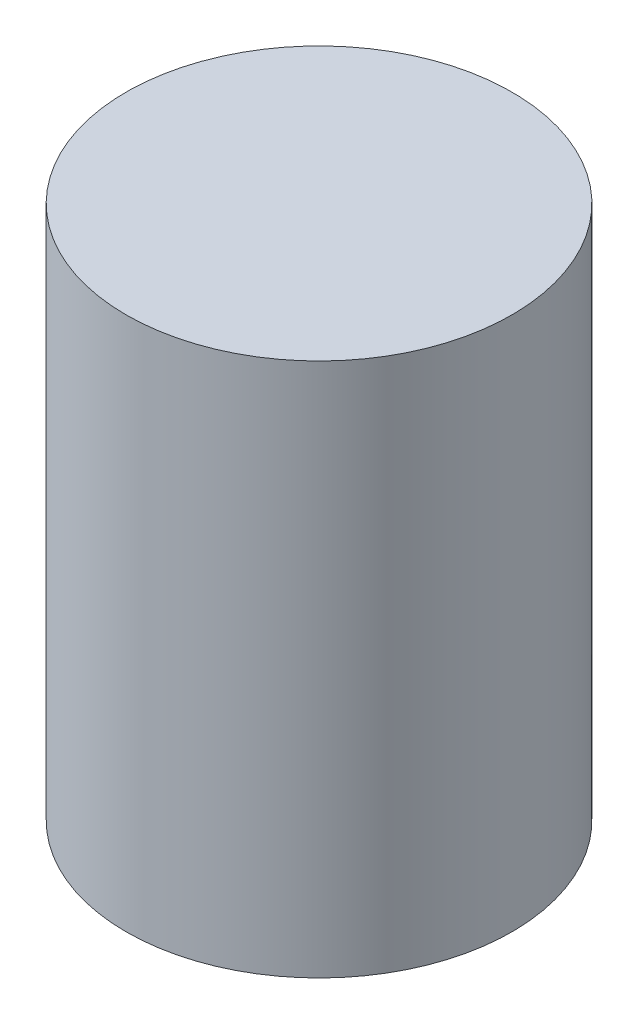
SolidWorks part; units mm, degrees
ref_plane "Спереди" through (0, 0, 0) normal (0, 0, 1) x (1, 0, 0)
ref_plane "Сверху" through (0, 0, 0) normal (0, 1, 0) x (1, 0, 0)
ref_plane "Справа" through (0, 0, 0) normal (1, 0, 0) x (0, 0, -1)
sketch "Sketch1" plane through (0, 0, 0) normal (0, 1, 0) x (1, 0, 0)
  circle A0 centre (0, 0) radius 6.5
  dimension "D1" = 13
extrude "Boss-Extrude1" add sketch "Sketch1" along normal blind 18
sketch "Sketch2" plane through (0, 0, 0) normal (0, -1, 0) x (1, 0, 0)
  circle A0 centre (0, 0) radius 5
  dimension "D1" = 10
extrude "Cut-Extrude1" cut sketch "Sketch2" against normal blind 4
sketch "Sketch3" plane through (0, 4, 0) normal (0, -1, 0) x (1, 0, 0)
  line L0 (-1.7321, -2.571) -> (3.0483, -0.5639)
  line L1 (0.6581, -1.5674) -> (-1.2001, 2.8583) construction
  circle A0 centre (0, 0) radius 3.1 construction
  arc A1 (-1.7321, -2.571) -> (3.0483, -0.5639) centre (0, 0) cw
  dimension "D1" = 6.2
  dimension "D2" = 4.8
extrude "Cut-Extrude2" cut sketch "Sketch3" against normal blind 12
chamfer "Chamfer1" distance 1 angle 30 1 edges at (0, 0, -5)
